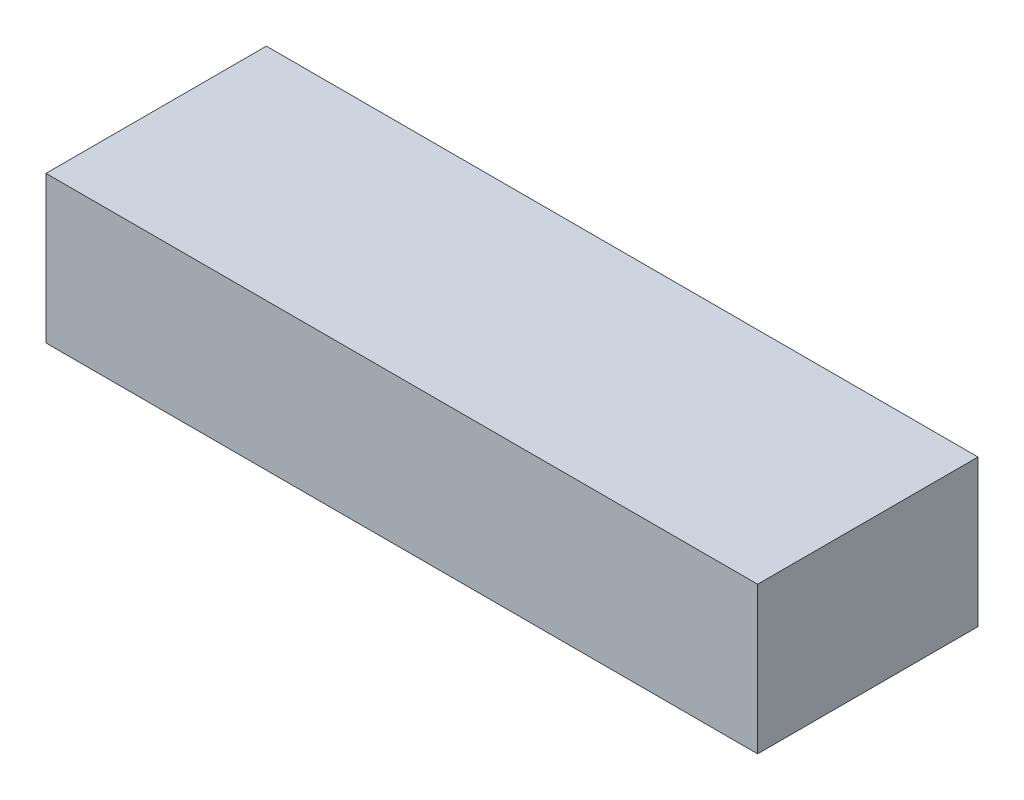
SolidWorks part; units mm, degrees
ref_plane "Front Plane" through (0, 0, 0) normal (0, 0, 1) x (1, 0, 0)
ref_plane "Top Plane" through (0, 0, 0) normal (0, 1, 0) x (1, 0, 0)
ref_plane "Right Plane" through (0, 0, 0) normal (1, 0, 0) x (0, 0, -1)
sketch "Sketch1" plane through (0, 0, 0) normal (0, 1, 0) x (1, 0, 0)
  line L1 (77.5, 24) -> (-77.5, 24)
  line L2 (77.5, 24) -> (77.5, -24)
  line L3 (77.5, -24) -> (-77.5, -24)
  line L4 (-77.5, 24) -> (-77.5, -24)
  line L5 (77.5, 24) -> (-77.5, -24) construction
  line L6 (77.5, -24) -> (-77.5, 24) construction
  point P0 (0, 0)
  dimension "D1" = 155
  dimension "D2" = 48
extrude "Boss-Extrude1" add sketch "Sketch1" along normal mid plane 32 separate body
